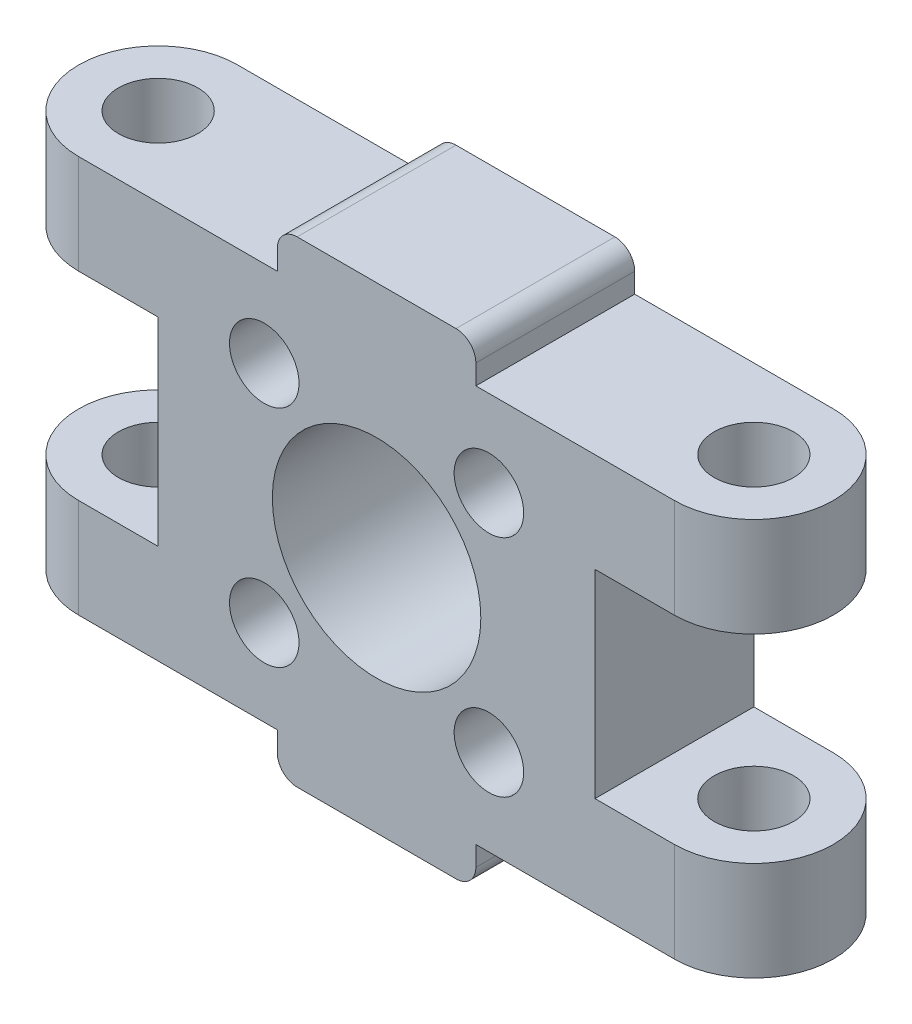
SolidWorks part; units mm, degrees
material "ABS"
ref_plane "Front Plane" through (0, 0, 0) normal (0, 0, 1) x (1, 0, 0)
ref_plane "Top Plane" through (0, 0, 0) normal (0, 1, 0) x (1, 0, 0)
ref_plane "Right Plane" through (0, 0, 0) normal (1, 0, 0) x (0, 0, -1)
sketch "Sketch1" plane through (0, 0, 0) normal (0, 1, 0) x (1, 0, 0)
  line L0 (-15, 0) -> (15, 0) construction
  line L1 (15, 4) -> (-15, 4)
  line L2 (-15, -4) -> (-15, 4) construction
  line L3 (15, -4) -> (-15, -4)
  line L4 (15, 4) -> (15, -4) construction
  circle A0 centre (-15, 0) radius 2
  circle A1 centre (15, 0) radius 2
  arc A2 (-15, 4) -> (-15, -4) centre (-15, 0) ccw
  arc A3 (15, -4) -> (15, 4) centre (15, 0) ccw
  point P0 (0, 0)
  dimension "D3" = 4
  dimension "D5" = 4
  dimension "D1" = 30
extrude "Boss-Extrude1" add sketch "Sketch1" along normal mid plane 20
sketch "Sketch2" plane through (0, 0, 4) normal (0, 0, 1) x (1, 0, 0)
  line L0 (-5, -9.798) -> (-5, -12)
  line L1 (5, 12) -> (-5, 12)
  line L2 (5, 12) -> (5, 9.798)
  line L3 (5, -9.798) -> (5, -12)
  line L5 (5, -12) -> (-5, -12)
  line L6 (-5, 12) -> (-5, 9.798)
  line L7 (5, 12) -> (-5, -12) construction
  line L8 (5, -12) -> (-5, 12) construction
  arc A0 (-5, 9.798) -> (-5, -9.798) centre (0, 0) ccw
  arc A1 (5, -9.798) -> (5, 9.798) centre (0, 0) ccw
  dimension "D1" = 22
  dimension "D2" = 12
  dimension "D3" = 10
sketch "Sketch3" plane through (0, 0, 4) normal (0, 0, 1) x (1, 0, 0)
  line L0 (-19, 10) -> (-19, -10) construction
  line L1 (-19, 5) -> (-11, 5)
  line L2 (-19, 5) -> (-19, -5)
  line L3 (-19, -5) -> (-11, -5)
  line L4 (-11, 5) -> (-11, -5)
  line L5 (0, 10) -> (0, -10) construction
  line L6 (-15, 10) -> (15, 10) construction
  line L7 (-15, -10) -> (15, -10) construction
  line L8 (11, 5) -> (11, -5)
  line L9 (19, -5) -> (11, -5)
  line L10 (19, 5) -> (19, -5)
  line L11 (19, 5) -> (11, 5)
  point P10 (11, 0)
  point P11 (-11, 0)
  dimension "D1" = 11
  dimension "D2" = 10
extrude "Cut-Extrude2" cut sketch "Sketch3" against normal up to surface (8 mm away) up to face at (0, 0, -4)
extrude "Boss-Extrude2" add sketch "Sketch2" against normal up to surface (8 mm away) up to face at (0, 0, -4)
sketch "Sketch4" plane through (0, 0, 4) normal (0, 0, 1) x (1, 0, 0)
  point P0 (0, 0)
hole_wizard "Ø10.5 (10.5) Diameter Hole1" positions "3DSketch1" profile "Sketch5" hole size "Ø10.5" standard "ANSI Metric" end condition up to next
sketch3d "3DSketch1"
  point P0 (0, 0, 4)
sketch "Sketch5" plane through (0, 0, 4) normal (1, 0, 0) x (0, -1, 0)
  line L0 (0, 0) -> (0, 8)
  line L1 (0, 8) -> (5.25, 8)
  line L2 (5.25, 8) -> (5.25, 0)
  line L5 (5.25, 0) -> (0, 0)
  line L11 (0, -6.35) -> (0, 107.95) construction
  dimension "Thru Hole Dia." = 10.5
  dimension "Thru Hole Depth" = 8
sketch "Sketch6" plane through (0, 0, 4) normal (0, 0, 1) x (1, 0, 0)
  line L0 (5.6569, 5.6569) -> (-5.6569, -5.6569) construction
  line L1 (-5.6569, -5.6569) -> (-5.6569, 5.6569) construction
  line L2 (-5.6569, 5.6569) -> (5.6569, -5.6569) construction
  circle A0 centre (0, 0) radius 8 construction
  point P13 (5.6569, 5.6569)
  point P14 (5.6569, -5.6569)
  point P15 (-5.6569, -5.6569)
  point P16 (-5.6569, 5.6569)
  dimension "D1" = 45
  dimension "D2" = 16
hole_wizard "Ø3.5 (3.5) Diameter Hole1" positions "3DSketch2" profile "Sketch7" hole size "Ø3.5" standard "ANSI Metric" end condition up to next
sketch3d "3DSketch2"
  point P12 (5.6569, 5.6569, 4)
  point P15 (5.6569, -5.6569, 4)
  point P18 (-5.6569, 5.6569, 4)
  point P21 (-5.6569, -5.6569, 4)
sketch "Sketch7" plane through (5.6569, 5.6569, 4) normal (1, 0, 0) x (0, -1, 0)
  line L0 (0, 0) -> (0, 8)
  line L1 (0, 8) -> (1.75, 8)
  line L2 (1.75, 8) -> (1.75, 0)
  line L5 (1.75, 0) -> (0, 0)
  line L11 (0, -6.35) -> (0, 107.95) construction
  dimension "Thru Hole Dia." = 3.5
  dimension "Thru Hole Depth" = 8
fillet "Fillet1" radius 1 4 edges at (-5, -12, 0) (5, -12, 0) (-5, 12, 0) (5, 12, 0)
